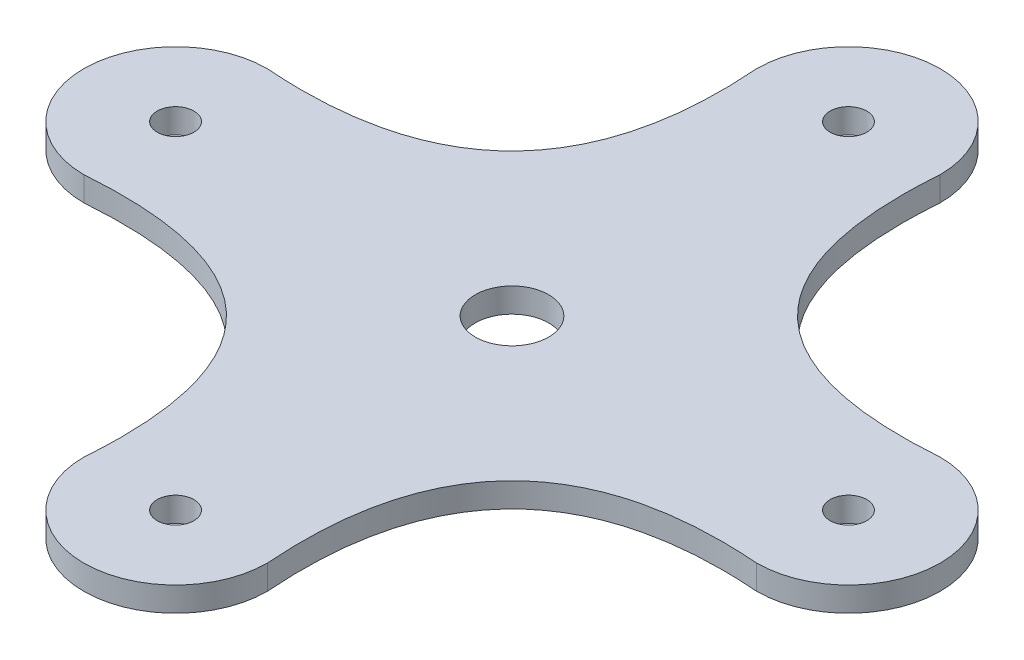
SolidWorks part; units mm, degrees
ref_plane "Front Plane" through (0, 0, 0) normal (0, 0, 1) x (1, 0, 0)
ref_plane "Top Plane" through (0, 0, 0) normal (0, 1, 0) x (1, 0, 0)
ref_plane "Right Plane" through (0, 0, 0) normal (1, 0, 0) x (0, 0, -1)
sketch "Sketch1" plane through (0, 0, 0) normal (0, 1, 0) x (1, 0, 0)
  line L0 (-27.5, 0) -> (27.5, 0) construction
  line L1 (0, -27.5) -> (0, 27.5) construction
  line L2 (-35, 0) -> (35, 0) construction
  line L3 (0, -35) -> (0, 35) construction
  line L4 (-47.4415, 47.4415) -> (47.4415, -47.4415) construction
  line L5 (-45.3102, -45.3102) -> (45.3102, 45.3102) construction
  circle A0 centre (0, 27.5) radius 1.5
  circle A1 centre (-27.5, 0) radius 1.5
  circle A2 centre (27.5, 0) radius 1.5
  circle A3 centre (0, -27.5) radius 1.5
  circle A8 centre (0, 0) radius 16.5 construction
  circle A9 centre (0, 0) radius 3
  arc A10 (-27.5, 7.5) -> (-27.5, -7.5) centre (-27.5, 0) ccw
  arc A11 (-7.5, -27.5) -> (7.5, -27.5) centre (0, -27.5) ccw
  arc A12 (7.5, 27.5) -> (-7.5, 27.5) centre (0, 27.5) ccw
  arc A13 (27.5, -7.5) -> (27.5, 7.5) centre (27.5, 0) ccw
  spline S0 degree 2 poles (-7.5, 27.5) (-5.8345, 5.8345) (-27.5, 7.5) knots 0 0 0 1 1 1
  spline S1 degree 2 poles (-27.5, -7.5) (-5.8345, -5.8345) (-7.5, -27.5) knots 0 0 0 1 1 1
  spline S2 degree 2 poles (7.5, -27.5) (5.8345, -5.8345) (27.5, -7.5) knots 0 0 0 1 1 1
  spline S3 degree 2 poles (27.5, 7.5) (5.8345, 5.8345) (7.5, 27.5) knots 0 0 0 1 1 1
  point P4 (0, 0)
  point P7 (0, 0)
  point P14 (0, 0)
  point P17 (0, 0)
  point P26 (0, 0)
  point P29 (0, 0)
  dimension "D3" = 70
  dimension "D5" = 45
  dimension "D1" = 55
  dimension "D2" = 55
  dimension "D4" = 70
  dimension "D6" = 45
extrude "Boss-Extrude1" add sketch "Sketch1" along normal blind 2 contours A13 S3 A12 S0 A10 S1 A11 S2 A0 A1 A2 A3 A9
